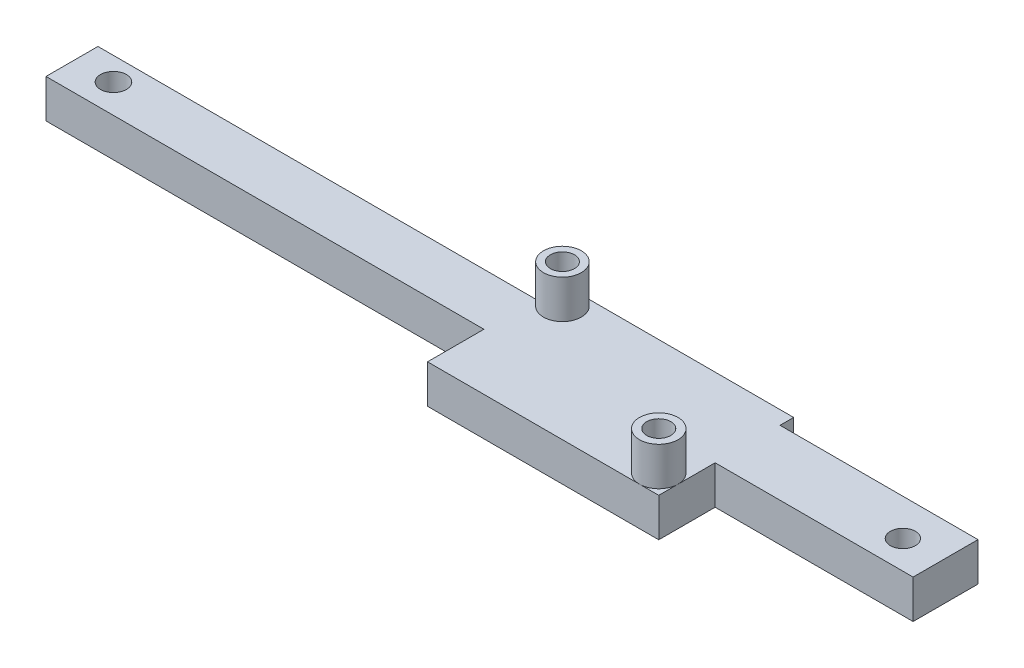
SolidWorks part; units mm, degrees
ref_plane "Front Plane" through (0, 0, 0) normal (0, 0, 1) x (1, 0, 0)
ref_plane "Top Plane" through (0, 0, 0) normal (0, 1, 0) x (1, 0, 0)
ref_plane "Right Plane" through (0, 0, 0) normal (1, 0, 0) x (0, 0, -1)
sketch "Sketch1" plane through (0, 0, 0) normal (0, 1, 0) x (1, 0, 0)
  line L1 (-0.5646, 0.1333) -> (29.9154, 0.1333)
  line L2 (-0.5646, 0.1333) -> (-0.5646, -17.6467)
  line L3 (-0.5646, -17.6467) -> (29.9154, -17.6467)
  line L4 (29.9154, 0.1333) -> (29.9154, -17.6467)
  dimension "D2" = 30.48
  dimension "D3" = 17.78
extrude "Boss-Extrude1" add sketch "Sketch1" along normal blind 5.08
sketch "Sketch3" plane through (0, 5.08, 0) normal (0, 1, 0) x (1, 0, 0)
  line L0 (29.9154, 0.1333) -> (-0.5646, 0.1333) construction
  line L1 (-0.5646, 0.1333) -> (-0.5646, -17.6467) construction
  circle A0 centre (1.9754, -2.4067) radius 1.5875
  circle A1 centre (27.3754, -15.1067) radius 1.5875
  dimension "D1" = 3.175
  dimension "D2" = 25.4
  dimension "D3" = 12.7
  dimension "D4" = 2.54
  dimension "D5" = 2.54
extrude "Cut-Extrude1" cut sketch "Sketch3" against normal through all
sketch "Sketch4" plane through (0, 5.08, 0) normal (0, 1, 0) x (1, 0, 0)
  circle A0 centre (1.9754, -2.4067) radius 2.4966
  circle A1 centre (27.3754, -15.1067) radius 2.54
  circle A2 centre (1.9754, -2.4067) radius 1.5875
  circle A3 centre (27.3754, -15.1067) radius 1.5875
extrude "Boss-Extrude2" add sketch "Sketch4" along normal blind 5.08
sketch "Sketch6" plane through (0, 5.08, 0) normal (0, 1, 0) x (1, 0, 0)
  line L0 (29.9154, -15.1067) -> (29.9154, 0.1333) construction
  line L1 (29.9154, -10.2151) -> (56.0104, -10.2151)
  line L2 (29.9154, -10.2151) -> (29.9154, -1.6613)
  line L3 (29.9154, -1.6613) -> (56.0104, -1.6613)
  line L4 (56.0104, -10.2151) -> (56.0104, -1.6613)
  line L5 (-58.2896, -10.2151) -> (56.0104, -10.2151) construction
  line L6 (56.0104, -10.2151) -> (56.0104, 30.3459) construction
  circle A0 centre (50.9304, -6.4841) radius 1.6464
extrude "Boss-Extrude3" add sketch "Sketch6" against normal blind 5.08
sketch "Sketch7" plane through (0, 5.08, 0) normal (0, 1, 0) x (1, 0, 0)
  line L1 (-58.2896, -10.2151) -> (-0.329, -10.2151)
  line L2 (-58.2896, -10.2151) -> (-58.2896, -3.3675)
  line L3 (-58.2896, -3.3675) -> (-0.329, -3.3675)
  line L4 (-0.329, -10.2151) -> (-0.329, -3.3675)
  circle A0 centre (1.9754, -2.4067) radius 2.4966 construction
  circle A2 centre (-53.2096, -6.4051) radius 1.7091
extrude "Boss-Extrude4" add sketch "Sketch7" against normal blind 5.08
